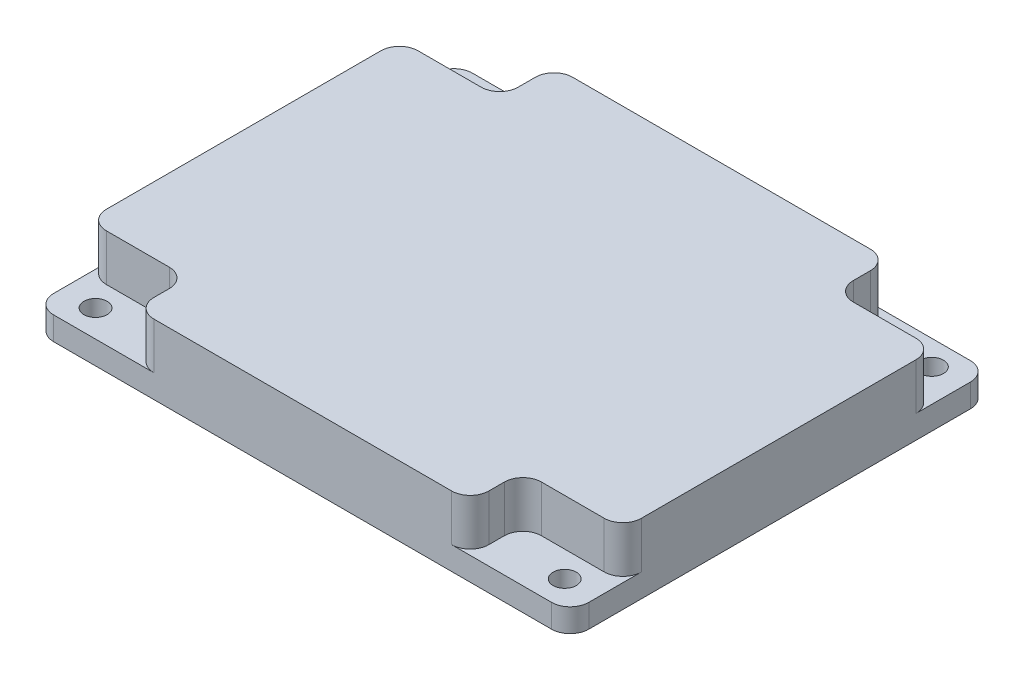
SolidWorks part; units mm, degrees
material "Стекло"
ref_plane "Спереди" through (0, 0, 0) normal (0, 0, 1) x (1, 0, 0)
ref_plane "Сверху" through (0, 0, 0) normal (0, 1, 0) x (1, 0, 0)
ref_plane "Справа" through (0, 0, 0) normal (1, 0, 0) x (0, 0, -1)
other "Configuration Table"
sketch "Эскиз1" plane through (0, 0, 0) normal (0, 1, 0) x (1, 0, 0)
  line L0 (57.2826, -44.7826) -> (-57.7174, -44.7826)
  line L1 (57.2826, -44.7826) -> (57.2826, 45.2174)
  line L2 (57.2826, 45.2174) -> (-57.7174, 45.2174)
  line L3 (-57.7174, -44.7826) -> (-57.7174, 45.2174)
extrude "Бобышка-Вытянуть1" add sketch "Эскиз1" along normal blind 15
sketch "Эскиз2" plane through (0, 0, 0) normal (0, -1, 0) x (1, 0, 0)
  line L1 (-55, 42.5) -> (55, 42.5)
  line L2 (-55, 42.5) -> (-55, -42.5)
  line L3 (-55, -42.5) -> (55, -42.5)
  line L4 (55, 42.5) -> (55, -42.5)
  line L5 (-55, 42.5) -> (55, -42.5) construction
  line L6 (-55, -42.5) -> (55, 42.5) construction
  point P0 (0, 0)
  dimension "D1" = 85
  dimension "D2" = 110
extrude "Вырез-Вытянуть1" cut sketch "Эскиз2" against normal blind 13
sketch "Эскиз4" plane through (0, 15, 0) normal (0, 1, 0) x (1, 0, 0)
  circle A0 centre (-50.1461, 38.945) radius 2.5
  circle A1 centre (50.6788, -39.9614) radius 2.5
  circle A2 centre (-50.1461, -39.9614) radius 2.5
  circle A3 centre (50.6788, 38.945) radius 2.5
extrude "Вырез-Вытянуть2" cut sketch "Эскиз4" against normal blind 13
sketch "Эскиз5" plane through (0, 15, 0) normal (0, 1, 0) x (1, 0, 0)
  line L2 (-56.1904, 33.5328) -> (-36.1904, 33.5328)
  line L3 (-36.1904, 43.5328) -> (-36.1904, 33.5328)
  line L6 (-56.1904, -33.4672) -> (-36.1904, -33.4672)
  line L7 (-36.1904, -43.4672) -> (-36.1904, -33.4672)
  line L10 (55.8096, -33.4672) -> (35.8096, -33.4672)
  line L11 (35.8096, -43.4672) -> (35.8096, -33.4672)
  line L14 (55.8096, 33.5328) -> (35.8096, 33.5328)
  line L15 (35.8096, 43.5328) -> (35.8096, 33.5328)
  line L16 (-36.1904, -43.4672) -> (-36.1904, -44.7826)
  line L17 (-57.7174, -44.7826) -> (57.2826, -44.7826) construction
  line L18 (-36.1904, -44.7826) -> (-57.7174, -44.7826)
  line L19 (-57.7174, -44.7826) -> (-57.7174, -33.4672)
  line L20 (-57.7174, 45.2174) -> (-57.7174, -44.7826) construction
  line L21 (-57.7174, -33.4672) -> (-56.1904, -33.4672)
  line L22 (55.8096, -33.4672) -> (57.2826, -33.4672)
  line L23 (57.2826, -44.7826) -> (57.2826, 45.2174) construction
  line L24 (57.2826, -33.4672) -> (57.2826, -44.7826)
  line L25 (57.2826, -44.7826) -> (35.8096, -44.7826)
  line L26 (35.8096, -44.7826) -> (35.8096, -43.4672)
  line L27 (35.8096, 43.5328) -> (35.8096, 45.2174)
  line L28 (57.2826, 45.2174) -> (-57.7174, 45.2174) construction
  line L29 (35.8096, 45.2174) -> (57.2826, 45.2174)
  line L30 (57.2826, 45.2174) -> (57.2826, 33.5328)
  line L31 (57.2826, 33.5328) -> (55.8096, 33.5328)
  line L32 (-56.1904, 33.5328) -> (-57.7174, 33.5328)
  line L33 (-57.7174, 33.5328) -> (-57.7174, 45.2174)
  line L34 (-57.7174, 45.2174) -> (-36.1904, 45.2174)
  line L35 (-36.1904, 45.2174) -> (-36.1904, 43.5328)
extrude "Вырез-Вытянуть3" cut sketch "Эскиз5" against normal blind 10
sketch "Эскиз6" plane through (0, 13, 0) normal (0, -1, 0) x (1, 0, 0)
  line L0 (-55, -33.5328) -> (-36.1904, -33.5328)
  line L1 (-36.1904, -33.5328) -> (-36.1904, -42.5)
  line L2 (-36.1904, -42.5) -> (-34.1904, -42.5)
  line L3 (-36.1904, -42.5) -> (35.8096, -42.5) construction
  line L4 (-34.1904, -42.5) -> (-34.1904, -31.5574)
  line L5 (-55, -33.5328) -> (-55, -31.5328)
  line L6 (-55, 33.4672) -> (-55, -33.5328) construction
  line L7 (-55, -31.5328) -> (-35.5003, -31.5328)
  line L8 (-35.5003, -31.5328) -> (-34.1904, -31.5328)
  line L9 (-34.1904, -31.5574) -> (-34.1904, -31.5328)
  line L10 (-36.1904, 42.5) -> (-34.1904, 42.5)
  line L11 (35.8096, 42.5) -> (-36.1904, 42.5) construction
  line L12 (-55, 33.4672) -> (-55, 31.4672)
  line L13 (-55, 42.5) -> (-55, -42.5) construction
  line L14 (-55, 31.4672) -> (-34.1904, 31.4672)
  line L15 (-34.1904, 42.5) -> (-34.1904, 31.4672)
  line L16 (-55, 33.4672) -> (-36.1904, 33.4672)
  line L17 (-36.1904, 33.4672) -> (-36.1904, 42.5)
  line L18 (35.8096, 42.5) -> (33.8096, 42.5)
  line L19 (55, 33.4672) -> (55, 31.4672)
  line L20 (55, -42.5) -> (55, 42.5) construction
  line L21 (33.8096, 42.5) -> (33.8096, 31.4672)
  line L22 (33.8096, 31.4672) -> (55, 31.4672)
  line L23 (55, 33.4672) -> (35.8096, 33.4672)
  line L24 (35.8096, 33.4672) -> (35.8096, 42.5)
  line L25 (35.8096, -42.5) -> (33.8096, -42.5)
  line L26 (33.8096, -42.5) -> (33.8096, -31.5574)
  line L27 (33.8096, -31.5574) -> (55, -31.5574)
  line L28 (55, -33.5328) -> (55, 33.4672) construction
  line L29 (55, -31.5574) -> (55, -33.5328)
  line L30 (55, -33.5328) -> (35.8096, -33.5328)
  line L31 (35.8096, -33.5328) -> (35.8096, -42.5)
  dimension "D1" = 2
  dimension "D2" = 2
  dimension "D3" = 2
  dimension "D4" = 2
  dimension "D5" = 2
  dimension "D6" = 2
extrude "Бобышка-Вытянуть2" add sketch "Эскиз6" along normal blind 13
sketch "Эскиз8" plane through (0, 0, 0) normal (0, -1, 0) x (1, 0, 0)
  line L0 (57.2826, 44.7826) -> (57.2826, -45.2174) construction
  line L1 (-57.7174, 44.7826) -> (-34.1904, 44.7826)
  line L2 (-57.7174, 44.7826) -> (-57.7174, 31.4672)
  line L3 (-57.7174, 31.4672) -> (-34.1904, 31.4672)
  line L4 (-34.1904, 44.7826) -> (-34.1904, 31.4672)
  line L5 (33.8096, 31.4672) -> (57.2826, 31.4672)
  line L6 (33.8096, 31.4672) -> (33.8096, 44.7826)
  line L7 (33.8096, 44.7826) -> (57.2826, 44.7826)
  line L8 (57.2826, 31.4672) -> (57.2826, 44.7826)
  line L9 (33.8096, -31.5574) -> (57.2826, -31.5574)
  line L10 (33.8096, -31.5574) -> (33.8096, -45.2174)
  line L11 (33.8096, -45.2174) -> (57.2826, -45.2174)
  line L12 (57.2826, -31.5574) -> (57.2826, -45.2174)
  line L13 (57.2826, -45.2174) -> (-57.7174, -45.2174) construction
  line L14 (-34.1904, -31.5328) -> (-57.7174, -31.5328)
  line L15 (-34.1904, -31.5328) -> (-34.1904, -45.2174)
  line L16 (-34.1904, -45.2174) -> (-57.7174, -45.2174)
  line L17 (-57.7174, -31.5328) -> (-57.7174, -45.2174)
  line L18 (-57.7174, -45.2174) -> (-57.7174, 44.7826) construction
extrude "Бобышка-Вытянуть4" add sketch "Эскиз8" against normal blind 5
fillet "Скругление1" radius 4 16 edges at (-57.7174, 10, 33.4672) (-36.1904, 10, 33.4672) (-36.1904, 10, 44.7826) (-57.7174, 2.5, 44.7826) (-57.7174, 10, -33.5328) (-36.1904, 10, -33.5328) (-36.1904, 10, -45.2174) (-57.7174, 2.5, -45.2174) (35.8096, 10, -45.2174) (35.8096, 10, -33.5328) (57.2826, 10, -33.5328) (57.2826, 2.5, -45.2174) (35.8096, 10, 44.7826) (35.8096, 10, 33.4672) (57.2826, 10, 33.4672) (57.2826, 2.5, 44.7826)
fillet "Скругление2" radius 4 12 edges at (-55, 6.5, -31.5328) (-34.1904, 6.5, -42.5) (-34.1904, 6.5, -31.5328) (55, 6.5, -31.5574) (33.8096, 6.5, -42.5) (33.8096, 6.5, -31.5574) (33.8096, 6.5, 42.5) (55, 6.5, 31.4672) (33.8096, 6.5, 31.4672) (-55, 6.5, 31.4672) (-34.1904, 6.5, 42.5) (-34.1904, 6.5, 31.4672)
sketch "Эскиз9" plane through (0, 15, 0) normal (0, 1, 0) x (1, 0, 0)
  circle A0 centre (-50.5089, 39.9125) radius 2.5
  circle A1 centre (50.316, -38.9939) radius 2.5
  circle A2 centre (-50.5089, -38.9939) radius 2.5
  circle A3 centre (50.316, 39.9125) radius 2.5
extrude "Вырез-Вытянуть4" cut sketch "Эскиз9" against normal blind 25
